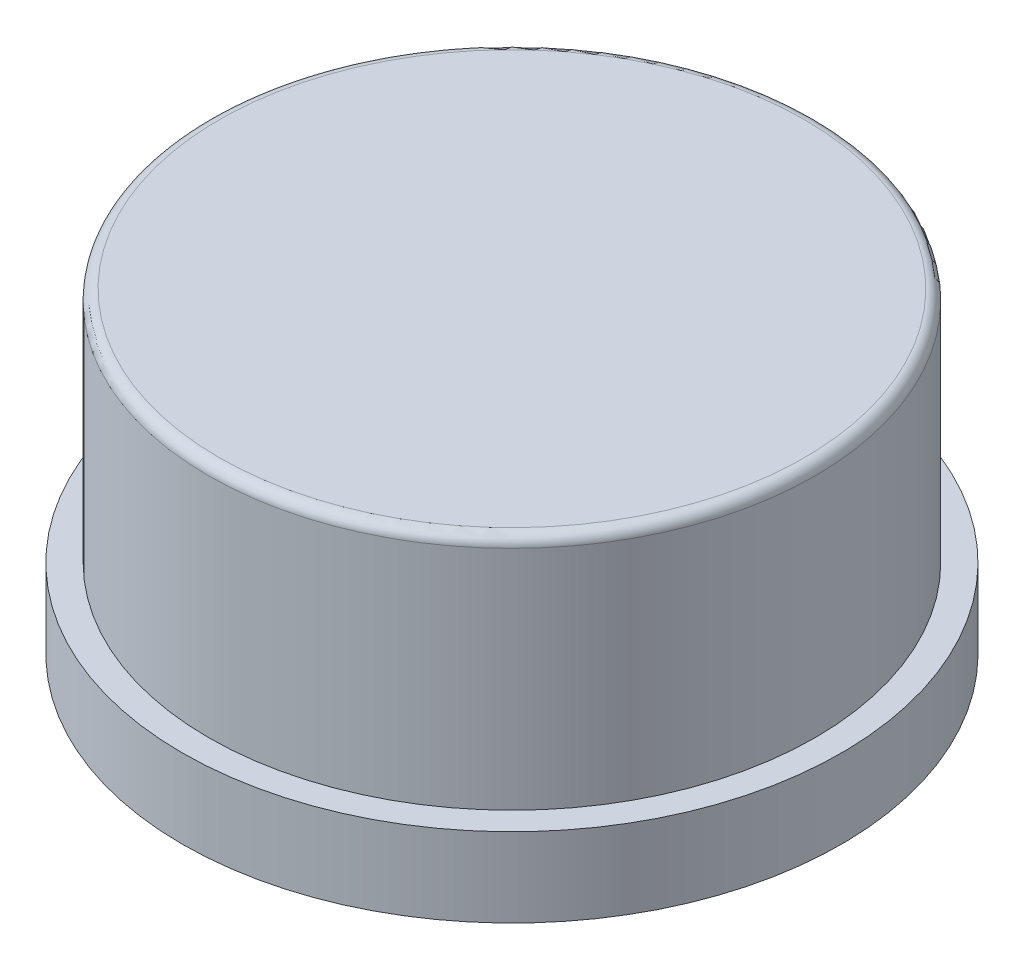
SolidWorks part; units mm, degrees
ref_plane "Front Plane" through (0, 0, 0) normal (0, 0, 1) x (1, 0, 0)
ref_plane "Top Plane" through (0, 0, 0) normal (0, 1, 0) x (1, 0, 0)
ref_plane "Right Plane" through (0, 0, 0) normal (1, 0, 0) x (0, 0, -1)
sketch "Sketch7" plane through (0, 0, 0) normal (0, 1, 0) x (1, 0, 0)
  circle A0 centre (0, 0) radius 6.25
  dimension "D1" = 12.5
extrude "Boss-Extrude2" add sketch "Sketch7" along normal blind 1.5
sketch "Sketch8" plane through (0, 1.5, 0) normal (0, 1, 0) x (1, 0, 0)
  circle A0 centre (0, 0) radius 5.75
  dimension "D1" = 11.5
extrude "Boss-Extrude3" add sketch "Sketch8" along normal blind 4.5 contours A0
fillet "Fillet4" radius 0.2 1 edges at (0, 6, 5.75)
sketch "Sketch9" plane through (0, 0, 0) normal (0, -1, 0) x (1, 0, 0)
  line L1 (2.5, -2.5) -> (-2.5, -2.5)
  line L2 (2.5, -2.5) -> (2.5, 2.5)
  line L3 (2.5, 2.5) -> (-2.5, 2.5)
  line L4 (-2.5, -2.5) -> (-2.5, 2.5)
  line L5 (2.5, -2.5) -> (-2.5, 2.5) construction
  line L6 (2.5, 2.5) -> (-2.5, -2.5) construction
  point P0 (0, 0)
  dimension "D1" = 5
  dimension "D2" = 5
extrude "Boss-Extrude4" add sketch "Sketch9" along normal blind 0.1 contours L3 L4 L1 L2
shell "Shell3" thickness 0.6
